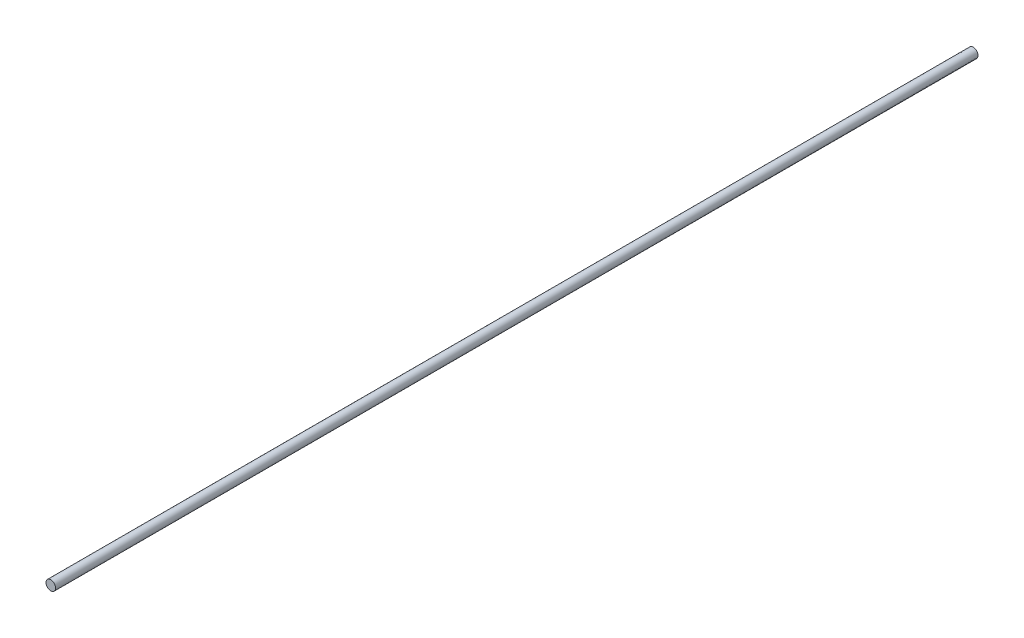
SolidWorks part; units mm, degrees
ref_plane "Front Plane" through (0, 0, 0) normal (0, 0, 1) x (1, 0, 0)
ref_plane "Top Plane" through (0, 0, 0) normal (0, 1, 0) x (1, 0, 0)
ref_plane "Right Plane" through (0, 0, 0) normal (1, 0, 0) x (0, 0, -1)
sketch "Length" plane through (0, 0, 0) normal (0, 1, 0) x (1, 0, 0)
  line L0 (0, 0) -> (0, -609.6)
  dimension "D1" = 609.6
sketch "Sketch1" plane through (0, 0, 0) normal (0, 0, 1) x (1, 0, 0)
  circle A0 centre (0, 0) radius 3.175
  dimension "D1" = 6.35
extrude "Boss-Extrude1" add sketch "Sketch1" along normal blind 609.6
equation "\"D1@Boss-Extrude1\"=\"D1@Length\""
